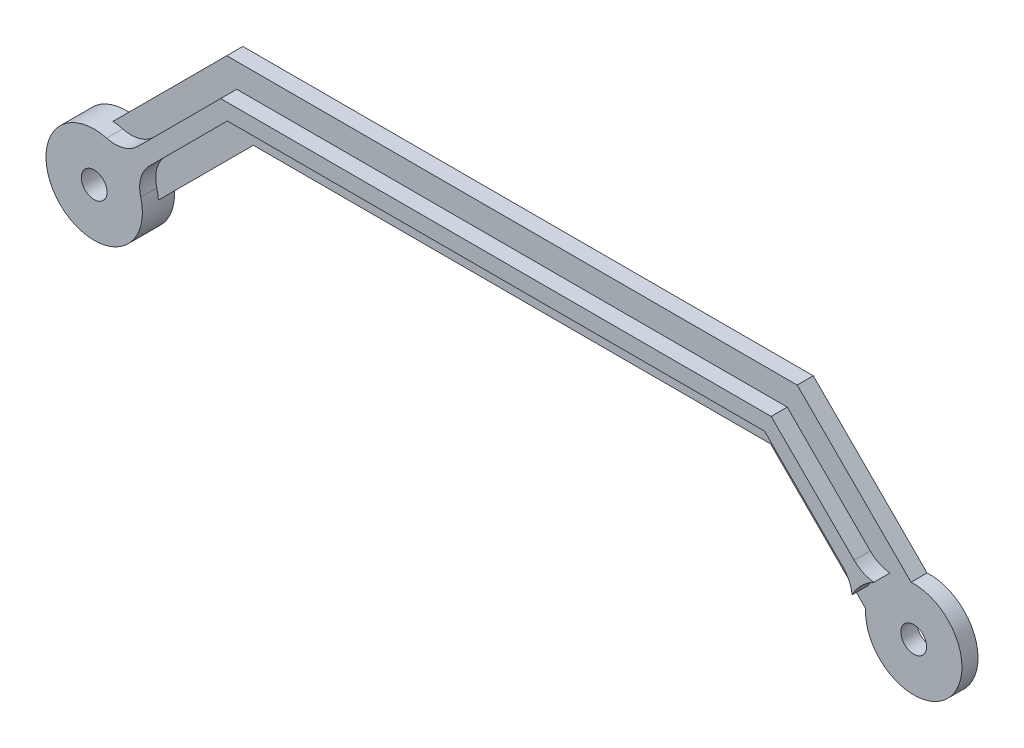
SolidWorks part; units mm, degrees
ref_plane "Ön Düzlem" through (0, 0, 0) normal (0, 0, 1) x (1, 0, 0)
ref_plane "Üst Düzlem" through (0, 0, 0) normal (0, 1, 0) x (1, 0, 0)
ref_plane "Sağ Düzlem" through (0, 0, 0) normal (1, 0, 0) x (0, 0, -1)
sketch "Sketch1" plane through (0, 0, 0) normal (0, 0, 1) x (1, 0, 0)
  line L0 (44.5393, 30.3971) -> (14.9768, 0.8346)
  line L2 (0.8346, 14.9768) -> (36.255, 50.3971)
  line L3 (249.1654, 14.9768) -> (213.745, 50.3971)
  line L5 (0, 0) -> (250, 0) construction
  line L6 (125, 0) -> (125, 50.3971) construction
  line L7 (205.4607, 30.3971) -> (235.0232, 0.8346)
  line L8 (44.5393, 30.3971) -> (205.4607, 30.3971)
  line L10 (36.255, 50.3971) -> (213.745, 50.3971)
  arc A0 (0.8346, 14.9768) -> (14.9768, 0.8346) centre (0, 0) ccw
  arc A1 (249.1654, 14.9768) -> (235.0232, 0.8346) centre (250, 0) cw
  circle A2 centre (0, 0) radius 4
  circle A3 centre (250, 0) radius 4
  dimension "D1" = 250
  dimension "D2" = 30
  dimension "D3" = 135
  dimension "D4" = 20
  dimension "D6" = 20
  dimension "D7" = 10
  dimension "D8" = 45
extrude "Boss-Extrude1" add sketch "Sketch1" along normal blind 5
sketch "Sketch6" plane through (0, 0, 5) normal (0, 0, 1) x (1, 0, 0)
  line L0 (249.1654, 14.9768) -> (213.745, 50.3971) construction
  line L1 (205.4607, 30.3971) -> (235.0232, 0.8346) construction
  line L2 (44.5393, 30.3971) -> (205.4607, 30.3971) construction
  line L3 (14.9768, 0.8346) -> (44.5393, 30.3971) construction
  line L4 (36.255, 50.3971) -> (0.8346, 14.9768) construction
  line L5 (213.745, 50.3971) -> (36.255, 50.3971) construction
  line L6 (249.1654, 14.9768) -> (213.745, 50.3971)
  line L7 (205.4607, 30.3971) -> (235.0232, 0.8346)
  line L8 (44.5393, 30.3971) -> (205.4607, 30.3971)
  line L9 (14.9768, 0.8346) -> (44.5393, 30.3971)
  line L10 (36.255, 50.3971) -> (0.8346, 14.9768)
  line L11 (213.745, 50.3971) -> (36.255, 50.3971)
  line L12 (243.8621, 9.6735) -> (210.6384, 42.8971)
  line L13 (210.6384, 42.8971) -> (39.3616, 42.8971)
  line L14 (39.3616, 42.8971) -> (6.1379, 9.6735)
  line L15 (9.6735, 6.1379) -> (41.4326, 37.8971)
  line L16 (41.4326, 37.8971) -> (208.5674, 37.8971)
  line L17 (208.5674, 37.8971) -> (240.3265, 6.1379)
  line L18 (6.1379, 9.6735) -> (9.6735, 6.1379)
  line L19 (243.8621, 9.6735) -> (240.3265, 6.1379)
  dimension "D1" = 7.5
extrude "Boss-Extrude2" add sketch "Sketch6" along normal blind 5 contours L13 L14 L18 L15 L16 L17 L19 L12
sketch "Sketch7" plane through (0, 0, 5) normal (0, 0, 1) x (1, 0, 0)
  circle A0 centre (0, 0) radius 4
  circle A1 centre (0, 0) radius 15
  circle A2 centre (250, 0) radius 4
  circle A3 centre (250, 0) radius 15
extrude "Boss-Extrude3" add sketch "Sketch7" along normal blind 5
fillet "Fillet1" radius 10 4 edges at (237.774, 8.6905, 7.5) (241.3095, 12.226, 7.5) (8.6905, 12.226, 7.5) (12.226, 8.6905, 7.5)
sketch "Çizim1" plane through (0, 0, 10) normal (0, 0, 1) x (1, 0, 0)
  circle A0 centre (250, 0) radius 16
extrude "Kes-Ekstrüzyon1" cut sketch "Çizim1" against normal blind 5
